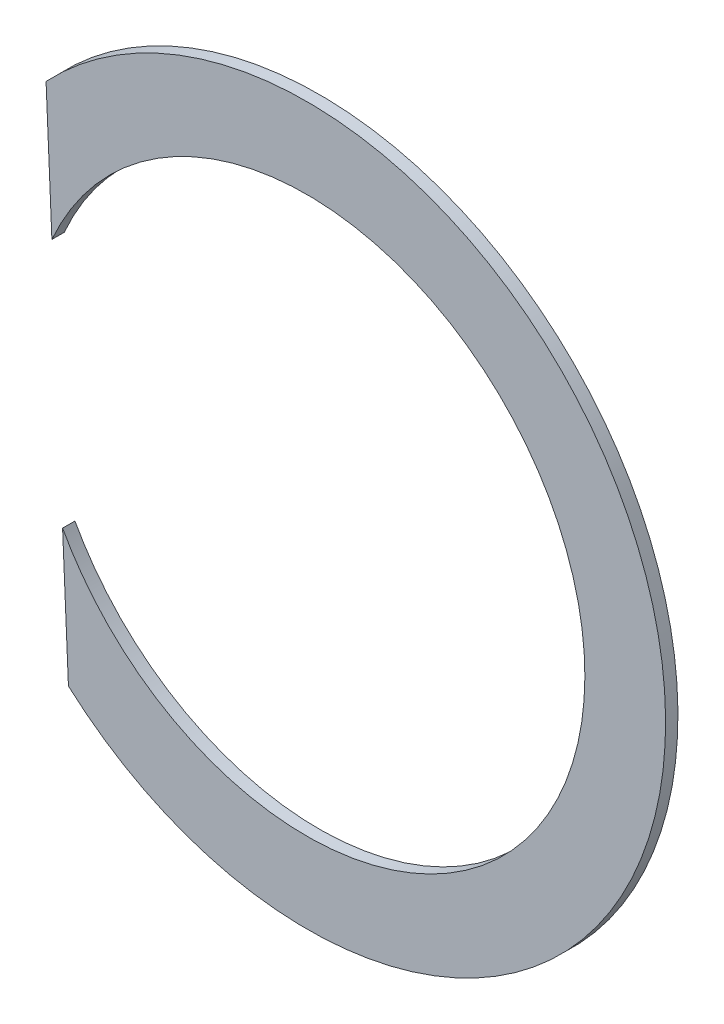
SolidWorks part; units mm, degrees
ref_plane "前视基准面" through (0, 0, 0) normal (0, 0, 1) x (1, 0, 0)
ref_plane "上视基准面" through (0, 0, 0) normal (0, 1, 0) x (1, 0, 0)
ref_plane "右视基准面" through (0, 0, 0) normal (1, 0, 0) x (0, 0, -1)
other "Configuration Table"
sketch "草图2" plane through (0, 0, 0) normal (0, 0, 1) x (1, 0, 0)
  line L0 (-22.0791, 20.2409) -> (-21.4841, 6.6137)
  line L1 (-20.231, -22.0882) -> (-20.8259, -8.461)
  arc A0 (-20.231, -22.0882) -> (-22.0791, 20.2409) centre (0.086, 0.0038) ccw
  ellipse E0 centre (0.0424, 0.0019) end of major axis (22.5424, 0.9842) minor radius 22.5 (-20.8259, -8.461) -> (-21.4841, 6.6137) ccw
sketch "草图3" plane through (0, 0, 0) normal (0, 0, 1) x (1, 0, 0)
  line L9 (-19.8269, -8.4173) -> (-19.2501, -21.6277)
  line L10 (-21.0618, 19.8677) -> (-20.4851, 6.6573)
  line L11 (-19.7235, -10.784) -> (-19.2501, -21.6277)
  line L12 (-21.0618, 19.8677) -> (-20.5884, 9.024)
  arc A6 (-19.2501, -21.6277) -> (-21.0618, 19.8677) centre (0.086, 0.0038) ccw
  arc A7 (-19.2501, -21.6277) -> (-21.0618, 19.8677) centre (0.086, 0.0038) ccw
  ellipse E2 centre (0.0424, 0.0019) end of major axis (22.5424, 0.9842) minor radius 22.5 (-20.8259, -8.461) -> (-21.4841, 6.6137) ccw construction
  ellipse E3 centre (0.0424, 0.0019) end of major axis (22.5424, 0.9842) minor radius 22.5 (-19.7235, -10.784) -> (-20.5884, 9.024) ccw
  point P13 (-19.7041, -10.8196)
  dimension "D1" = 1
extrude "凸台-拉伸1" add sketch "草图3" along normal blind 1
